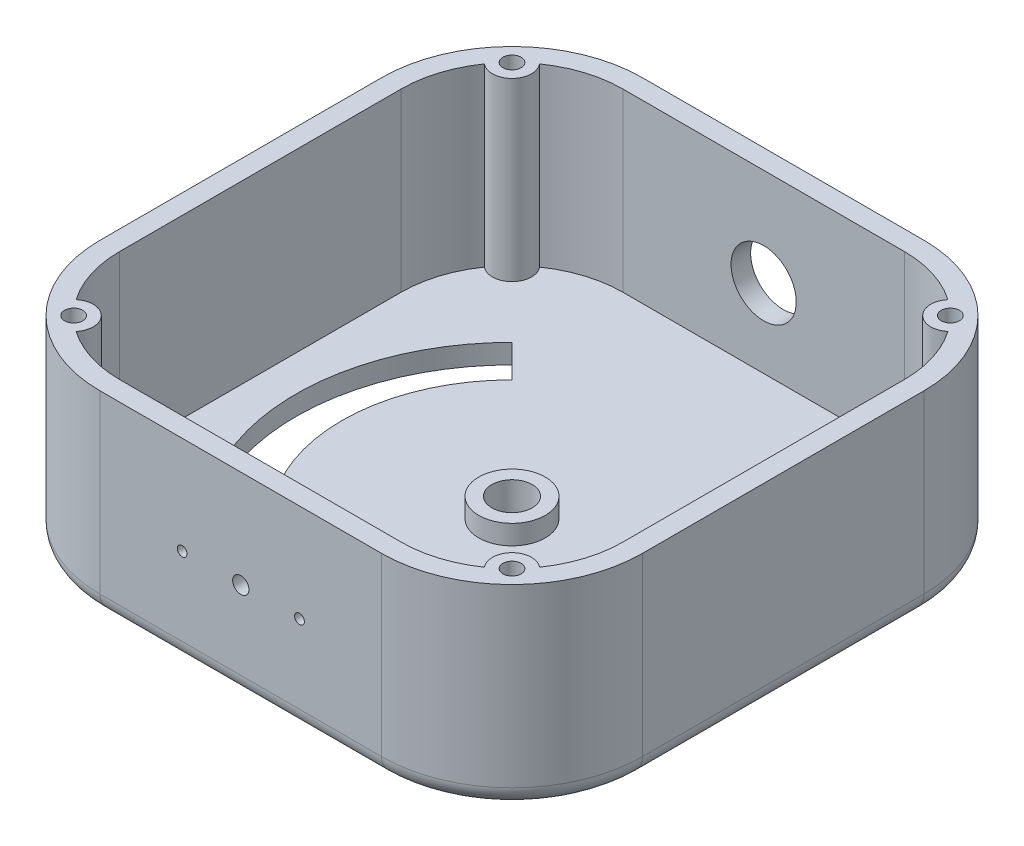
SolidWorks part; units mm, degrees
ref_plane "Front Plane" through (0, 0, 0) normal (0, 0, 1) x (1, 0, 0)
ref_plane "Top Plane" through (0, 0, 0) normal (0, 1, 0) x (1, 0, 0)
ref_plane "Right Plane" through (0, 0, 0) normal (1, 0, 0) x (0, 0, -1)
sketch "Sketch1" plane through (0, 0, 0) normal (0, 1, 0) x (1, 0, 0)
  line L1 (-61.062, 38.3158) -> (22.138, 38.3158)
  line L2 (-61.062, 38.3158) -> (-61.062, -44.8842)
  line L3 (-61.062, -44.8842) -> (22.138, -44.8842)
  line L4 (22.138, 38.3158) -> (22.138, -44.8842)
  dimension "D1" = 83.2
  dimension "D2" = 83.2
extrude "Boss-Extrude1" add sketch "Sketch1" along normal blind 30
fillet "Fillet1" radius 20 4 edges at (22.138, 15, 44.8842) (22.138, 15, -38.3158) (-61.062, 15, -38.3158) (-61.062, 15, 44.8842)
shell "Shell2" thickness 3
sketch "Sketch2" plane through (0, 0, 44.8842) normal (0, 0, 1) x (1, 0, 0)
  line L0 (-41.062, 30) -> (2.138, 30) construction
  circle A0 centre (-19.462, 15) radius 1.25
  circle A1 centre (-10.462, 15) radius 0.75
  circle A2 centre (-28.462, 15) radius 0.75
  point P8 (-19.462, 30)
  dimension "D1" = 2.5
  dimension "D2" = 1.5
  dimension "D3" = 1.5
  dimension "D4" = 9
  dimension "D5" = 9
  dimension "D6" = 0
extrude "Cut-Extrude1" cut sketch "Sketch2" against normal blind 30
sketch "Sketch3" plane through (0, 0, -38.3158) normal (0, 0, -1) x (-1, 0, 0)
  circle A0 centre (19.462, 15) radius 5
  dimension "D1" = 10
extrude "Cut-Extrude2" cut sketch "Sketch3" against normal blind 30
sketch "Sketch4" plane through (0, 0, 0) normal (0, -1, 0) x (1, 0, 0)
  line L0 (-42.9026, 26.7248) -> (-37.9175, 21.7397)
  line L1 (-42.9026, -20.1564) -> (-37.9175, -15.1713)
  line L2 (3.9786, 26.7248) -> (-1.0065, 21.7397)
  line L3 (3.9786, -20.1564) -> (-1.0065, -15.1713)
  line L4 (2.138, -38.3158) -> (-41.062, -38.3158) construction
  line L5 (-41.062, 44.8842) -> (2.138, 44.8842) construction
  line L6 (-61.062, -18.3158) -> (-61.062, 24.8842) construction
  circle A0 centre (-19.462, 3.2842) radius 33.15
  circle A1 centre (-19.462, 3.2842) radius 26.1
  circle A2 centre (-19.462, 3.2842) radius 3.1
  point P16 (-19.462, 44.8842)
  point P19 (-61.062, 3.2842)
  dimension "D1" = 6.2
  dimension "D2" = 66.3
  dimension "D3" = 52.2
  dimension "D8" = 0
  dimension "D9" = 0
  dimension "D4" = 90
  dimension "D5" = 45
  dimension "D6" = 90
  dimension "D7" = 90
extrude "Cut-Extrude3" cut sketch "Sketch4" against normal blind 30 contours A1 L3 A0 L2 | A1 L0 A0 L1 | A2
sketch "Sketch5" plane through (0, 0, 0) normal (0, -1, 0) x (1, 0, 0)
  line L0 (3.9786, -20.1564) -> (-1.0065, -15.1713) construction
  line L1 (-42.9026, 26.7248) -> (-37.9175, 21.7397)
  line L2 (-1.0065, 21.7397) -> (3.9786, 26.7248)
  line L3 (-1.0065, -15.1713) -> (3.9786, -20.1564)
  line L4 (-37.9175, -15.1713) -> (-42.9026, -20.1564)
  arc A0 (-1.0065, 21.7397) -> (-37.9175, 21.7397) centre (-19.462, 3.2842) ccw
  arc A1 (-37.9175, 21.7397) -> (-37.9175, -15.1713) centre (-19.462, 3.2842) ccw construction
  arc A2 (-42.9026, 26.7248) -> (3.9786, 26.7248) centre (-19.462, 3.2842) cw
  arc A3 (-37.9175, -15.1713) -> (-1.0065, -15.1713) centre (-19.462, 3.2842) ccw
  arc A4 (3.9786, -20.1564) -> (-42.9026, -20.1564) centre (-19.462, 3.2842) cw
  arc A5 (-42.9026, 26.7248) -> (-42.9026, -20.1564) centre (-19.462, 3.2842) ccw construction
extrude "Cut-Extrude4" cut sketch "Sketch5" against normal blind 1.2
sketch "Sketch6" plane through (0, 3, 0) normal (0, 1, 0) x (1, 0, 0)
  circle A0 centre (-19.462, -3.2842) radius 3.1
  circle A1 centre (-19.462, -3.2842) radius 5.1
  dimension "D1" = 2
extrude "Boss-Extrude2" add sketch "Sketch6" along normal blind 3
sketch "Sketch7" plane through (0, 3, 0) normal (0, 1, 0) x (1, 0, 0)
  circle A0 centre (-53.0828, 30.3366) radius 3
  arc A1 (-41.062, 35.3158) -> (-58.062, 18.3158) centre (-41.062, 18.3158) ccw construction
  circle A2 centre (-53.0828, -36.905) radius 3
  arc A3 (-58.062, -24.8842) -> (-41.062, -41.8842) centre (-41.062, -24.8842) ccw construction
  circle A4 centre (14.1588, -36.905) radius 3
  arc A5 (2.138, -41.8842) -> (19.138, -24.8842) centre (2.138, -24.8842) ccw construction
  circle A6 centre (14.1588, 30.3366) radius 3
  arc A7 (19.138, 18.3158) -> (2.138, 35.3158) centre (2.138, 18.3158) ccw construction
extrude "Boss-Extrude3" add sketch "Sketch7" along normal up to surface (27 mm away) up to face at (-19.462, 30, 3.2842)
sketch "Sketch9" plane through (0, 30, 0) normal (0, 1, 0) x (1, 0, 0)
  circle A0 centre (-53.0828, 30.3366) radius 1.4
  circle A1 centre (14.1588, 30.3366) radius 1.4
  circle A2 centre (14.1588, -36.905) radius 1.4
  circle A3 centre (-53.0828, -36.905) radius 1.4
  point P12 (-19.462, -3.2842)
  dimension "D1" = 2.8
  dimension "D2" = 4
extrude "Cut-Extrude5" cut sketch "Sketch9" against normal up to surface (27 mm away) up to face at (5.8245, 3, 3.2842)
fillet "Fillet2" radius 3 8 edges at (-61.062, 0, 3.2842) (-55.2041, 0, 39.0263) (-19.462, 0, 44.8842) (16.2801, 0, 39.0263) (22.138, 0, 3.2842) (16.2801, 0, -32.4579) (-19.462, 0, -38.3158) (-55.2041, 0, -32.4579)
